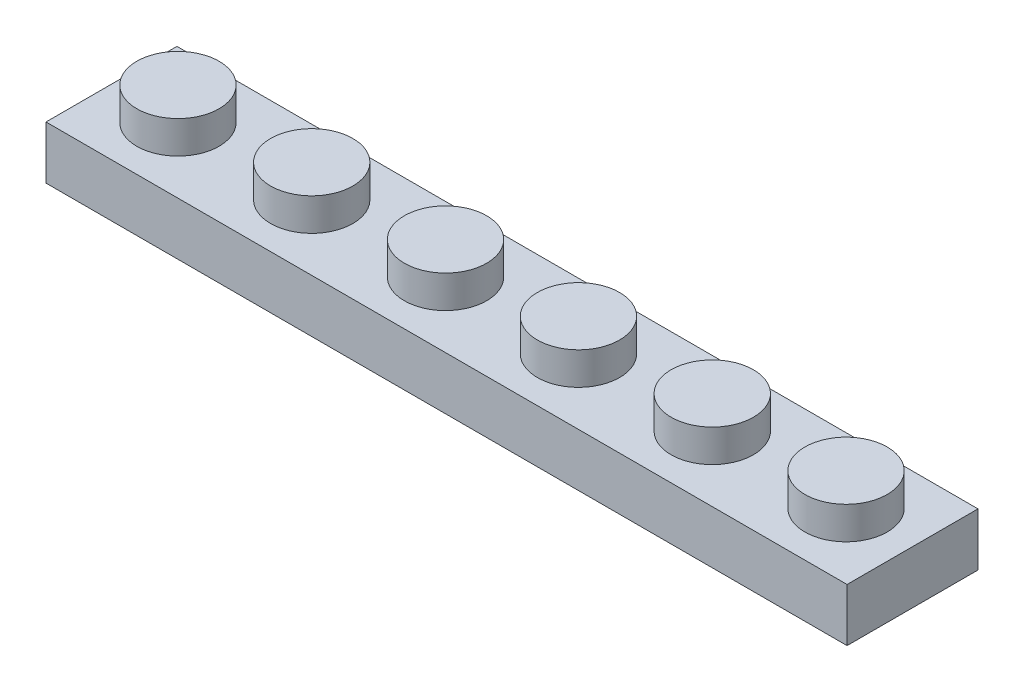
SolidWorks part; units mm, degrees
ref_plane "Front Plane" through (0, 0, 0) normal (0, 0, 1) x (1, 0, 0)
ref_plane "Top Plane" through (0, 0, 0) normal (0, 1, 0) x (1, 0, 0)
ref_plane "Right Plane" through (0, 0, 0) normal (1, 0, 0) x (0, 0, -1)
sketch "Sketch2" plane through (0, 0, 0) normal (0, 0, 1) x (1, 0, 0)
  line L1 (-23.89, 1.58) -> (23.89, 1.58)
  line L2 (-23.89, 1.58) -> (-23.89, -1.58)
  line L3 (-23.89, -1.58) -> (23.89, -1.58)
  line L4 (23.89, 1.58) -> (23.89, -1.58)
  line L5 (-23.89, 1.58) -> (23.89, -1.58) construction
  line L6 (-23.89, -1.58) -> (23.89, 1.58) construction
  point P0 (0, 0)
  dimension "D1" = 47.78
  dimension "D2" = 3.16
extrude "Boss-Extrude1" add sketch "Sketch2" against normal blind 7.81
sketch "Sketch3" plane through (0, 1.58, 0) normal (0, 1, 0) x (1, 0, 0)
  line L2 (23.89, 7.81) -> (-23.89, 7.81) construction
  line L3 (0, 13.2449) -> (0, -6.7525) construction
  line L6 (-11.945, 13.2449) -> (-11.945, -6.7525) construction
  line L7 (-23.89, 7.81) -> (-23.89, 0) construction
  circle A0 centre (-19.925, 3.905) radius 2.455
  circle A1 centre (-11.945, 3.905) radius 2.455
  circle A2 centre (-3.965, 3.905) radius 2.455
  circle A3 centre (3.965, 3.905) radius 2.455
  circle A4 centre (11.945, 3.905) radius 2.455
  circle A5 centre (19.925, 3.905) radius 2.455
  point P13 (0, 0)
  point P14 (-11.945, 3.2462)
  dimension "D1" = 4.91
  dimension "D4" = 7.98
  dimension "D5" = 7.98
  dimension "D2" = 3.905
  dimension "D3" = 11.945
extrude "Boss-Extrude2" add sketch "Sketch3" along normal blind 1.94
shell "Shell1" thickness 1.6
sketch "Sketch4" plane through (0, -0.02, 0) normal (0, -1, 0) x (1, 0, 0)
  line L1 (-23.89, 0) -> (23.89, 0) construction
  line L2 (0, 2.9923) -> (0, -9.6123) construction
  circle A0 centre (-15.935, -3.905) radius 1.495
  circle A1 centre (-15.935, -3.905) radius 0.595
  circle A2 centre (-19.925, -3.905) radius 0.855 construction
  circle A3 centre (-7.955, -3.905) radius 1.495
  circle A4 centre (-7.955, -3.905) radius 0.595
  circle A5 centre (-11.945, -3.905) radius 0.855 construction
  circle A6 centre (0, -3.905) radius 0.595
  circle A7 centre (0, -3.905) radius 1.495
  circle A8 centre (7.955, -3.905) radius 0.595
  circle A9 centre (7.955, -3.905) radius 1.495
  circle A10 centre (15.935, -3.905) radius 0.595
  circle A11 centre (15.935, -3.905) radius 1.495
  point P16 (0, 0)
  dimension "D2" = 3.99
  dimension "D3" = 2.99
  dimension "D4" = 1.19
  dimension "D5" = 3.99
  dimension "D6" = 0.595
  dimension "D7" = 1.495
  dimension "D1" = 3.905
extrude "Boss-Extrude3" add sketch "Sketch4" along normal offset from surface (1.36 mm away) 0.2 up to face at (0, -1.58, -3.905)
